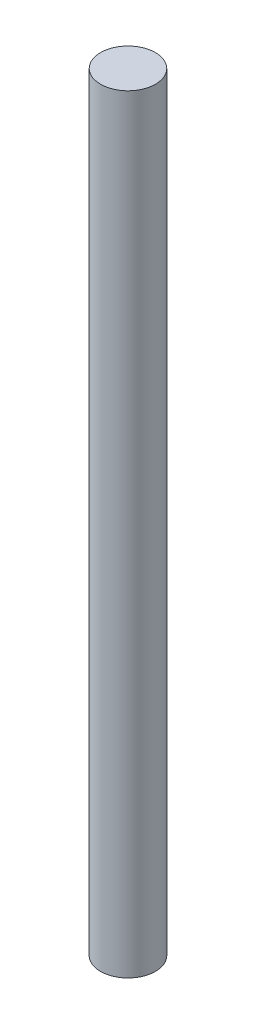
SolidWorks part; units mm, degrees
ref_plane "Front Plane" through (0, 0, 0) normal (0, 0, 1) x (1, 0, 0)
ref_plane "Top Plane" through (0, 0, 0) normal (0, 1, 0) x (1, 0, 0)
ref_plane "Right Plane" through (0, 0, 0) normal (1, 0, 0) x (0, 0, -1)
sketch "Sketch1" plane through (0, 0, 0) normal (0, 1, 0) x (1, 0, 0)
  circle A0 centre (0, 0) radius 1.5875
  dimension "D1" = 3.175
extrude "Boss-Extrude1" add sketch "Sketch1" along normal blind 44.45
